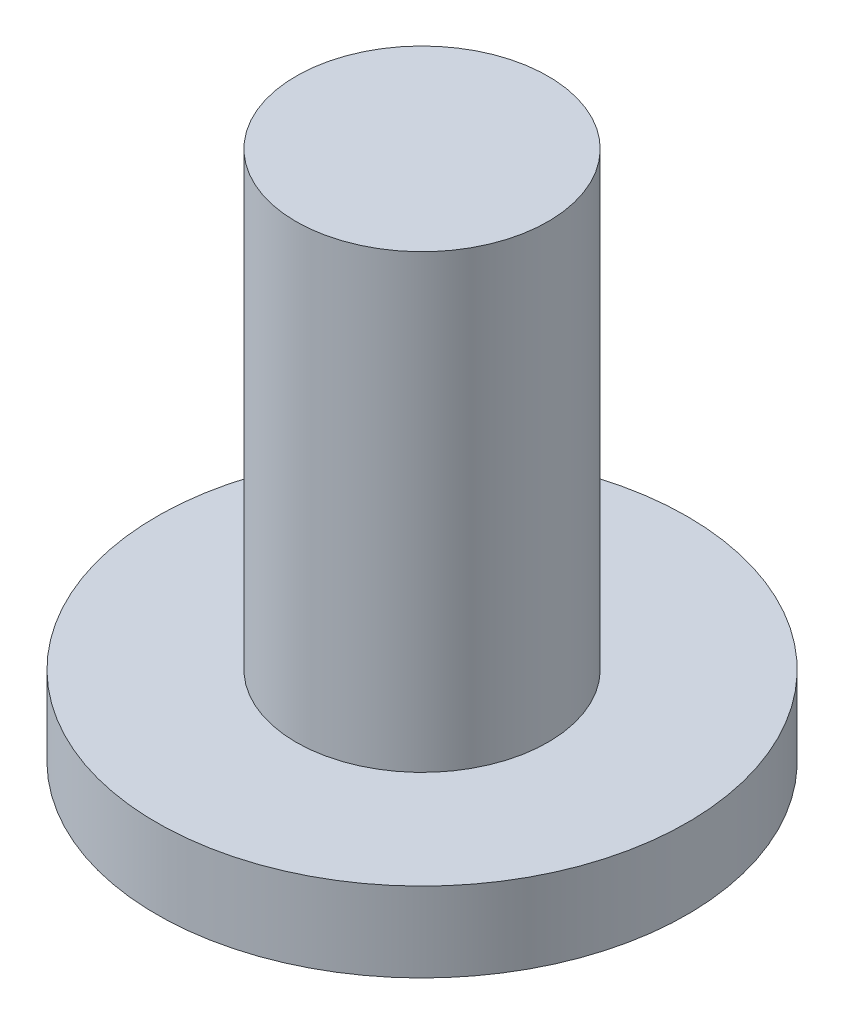
SolidWorks part; units mm, degrees
ref_plane "前视基准面" through (0, 0, 0) normal (0, 0, 1) x (1, 0, 0)
ref_plane "上视基准面" through (0, 0, 0) normal (0, 1, 0) x (1, 0, 0)
ref_plane "右视基准面" through (0, 0, 0) normal (1, 0, 0) x (0, 0, -1)
other "Configuration Table"
sketch "草图1" plane through (0, 0, 0) normal (0, 1, 0) x (1, 0, 0)
  circle A0 centre (0, 0) radius 4.75
  dimension "D1" = 9.5
extrude "凸台-拉伸1" add sketch "草图1" along normal blind 17
sketch "草图2" plane through (0, 0, 0) normal (0, -1, 0) x (1, 0, 0)
  circle A0 centre (0, 0) radius 10
  dimension "D1" = 20
extrude "凸台-拉伸2" add sketch "草图2" along normal blind 3
